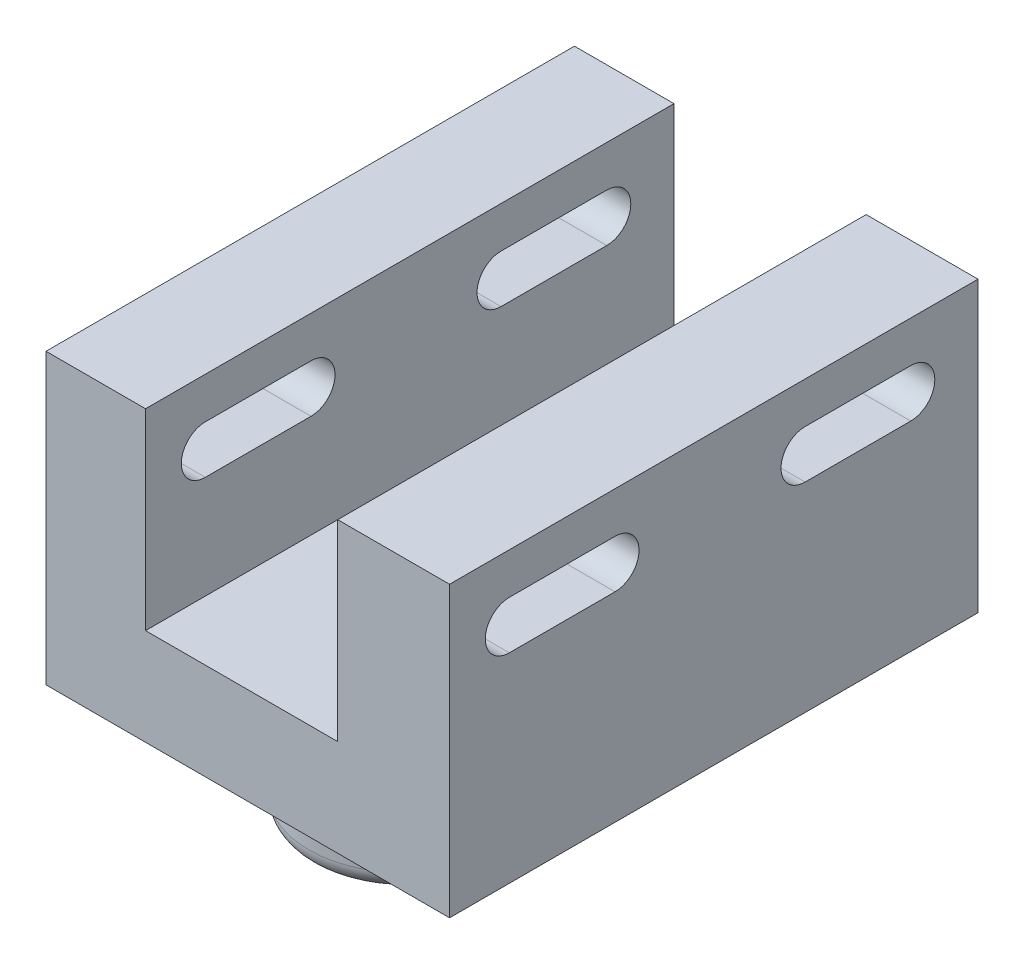
SolidWorks part; units mm, degrees
ref_plane "Front Plane" through (0, 0, 0) normal (0, 0, 1) x (1, 0, 0)
ref_plane "Top Plane" through (0, 0, 0) normal (0, 1, 0) x (1, 0, 0)
ref_plane "Right Plane" through (0, 0, 0) normal (1, 0, 0) x (0, 0, -1)
sketch "Sketch1" plane through (0, 0, 0) normal (0, 1, 0) x (1, 0, 0)
  line L0 (0, 0) -> (0, 25.4) construction
  line L1 (-12.7, 0) -> (-12.7, 25.4)
  line L2 (12.7, 0) -> (12.7, 25.4)
  arc A0 (-12.7, 0) -> (12.7, 0) centre (0, 0) ccw
  arc A1 (12.7, 25.4) -> (-12.7, 25.4) centre (0, 25.4) ccw
  point P3 (0, 12.7)
  dimension "D1" = 25.4
  dimension "D2" = 25.4
extrude "Boss-Extrude1" add sketch "Sketch1" along normal blind 6.35
sketch "Sketch2" plane through (0, 6.35, 0) normal (0, 1, 0) x (1, 0, 0)
  line L0 (0, 0) -> (0, 25.4) construction
  line L1 (-6.35, 0) -> (-6.35, 25.4)
  line L2 (6.35, 0) -> (6.35, 25.4)
  arc A0 (-6.35, 0) -> (6.35, 0) centre (0, 0) ccw
  arc A1 (6.35, 25.4) -> (-6.35, 25.4) centre (0, 25.4) ccw
  arc A2 (12.7, 25.4) -> (-12.7, 25.4) centre (0, 25.4) ccw construction
  point P3 (0, 12.7)
  dimension "D1" = 12.7
extrude "Boss-Extrude2" add sketch "Sketch2" along normal blind 6.604
sketch "Sketch3" plane through (0, 12.954, 0) normal (0, 1, 0) x (1, 0, 0)
  line L1 (-25.8574, 48.2561) -> (27.4826, 48.2561)
  line L2 (-25.8574, 48.2561) -> (-25.8574, -21.5939)
  line L3 (-25.8574, -21.5939) -> (27.4826, -21.5939)
  line L4 (27.4826, 48.2561) -> (27.4826, -21.5939)
  dimension "D1" = 69.85
  dimension "D2" = 53.34
extrude "Boss-Extrude3" add sketch "Sketch3" along normal blind 38.1857
fillet "Fillet1" radius 2.54 4 edges at (12.7, 0, -12.7) (0, 0, -38.1) (-12.7, 0, -12.7) (0, 0, 12.7)
sketch "Sketch4" plane through (0, 0, -48.2561) normal (0, 0, -1) x (-1, 0, 0)
  line L0 (-27.4826, 51.1397) -> (25.8574, 51.1397) construction
  line L1 (12.7, 51.1397) -> (-12.7, 51.1397)
  line L2 (12.7, 51.1397) -> (12.7, 25.7397)
  line L3 (12.7, 25.7397) -> (-12.7, 25.7397)
  line L4 (-12.7, 51.1397) -> (-12.7, 25.7397)
  point P6 (0, 25.7397)
  point P7 (0, 0)
  dimension "D1" = 25.4
  dimension "D2" = 25.4
extrude "Cut-Extrude1" cut sketch "Sketch4" against normal blind 70.358
sketch "Sketch5" plane through (27.4826, 0, 0) normal (1, 0, 0) x (0, 0, -1)
  line L0 (0.2779, 42.5146) -> (-13.6921, 42.5146) construction
  line L1 (0.2779, 39.3396) -> (-13.6921, 39.3396)
  line L2 (0.2779, 45.6896) -> (-13.6921, 45.6896)
  line L3 (25.4, 42.5146) -> (39.37, 42.5146) construction
  line L4 (25.4, 45.6896) -> (39.37, 45.6896)
  line L5 (25.4, 39.3396) -> (39.37, 39.3396)
  arc A0 (0.2779, 39.3396) -> (0.2779, 45.6896) centre (0.2779, 42.5146) ccw
  arc A1 (-13.6921, 45.6896) -> (-13.6921, 39.3396) centre (-13.6921, 42.5146) ccw
  arc A2 (25.4, 45.6896) -> (25.4, 39.3396) centre (25.4, 42.5146) ccw
  arc A3 (39.37, 39.3396) -> (39.37, 45.6896) centre (39.37, 42.5146) ccw
  point P2 (-6.7071, 42.5146)
  point P9 (32.385, 42.5146)
  point P14 (3.4529, 42.5146)
  point P15 (-16.8671, 42.5146)
  point P16 (22.225, 42.5146)
  point P17 (42.545, 42.5146)
  dimension "D3" = 20.32
  dimension "D1" = 6.35
  dimension "D2" = 6.35
  dimension "D4" = 20.32
extrude "Cut-Extrude2" cut sketch "Sketch5" against normal through all
